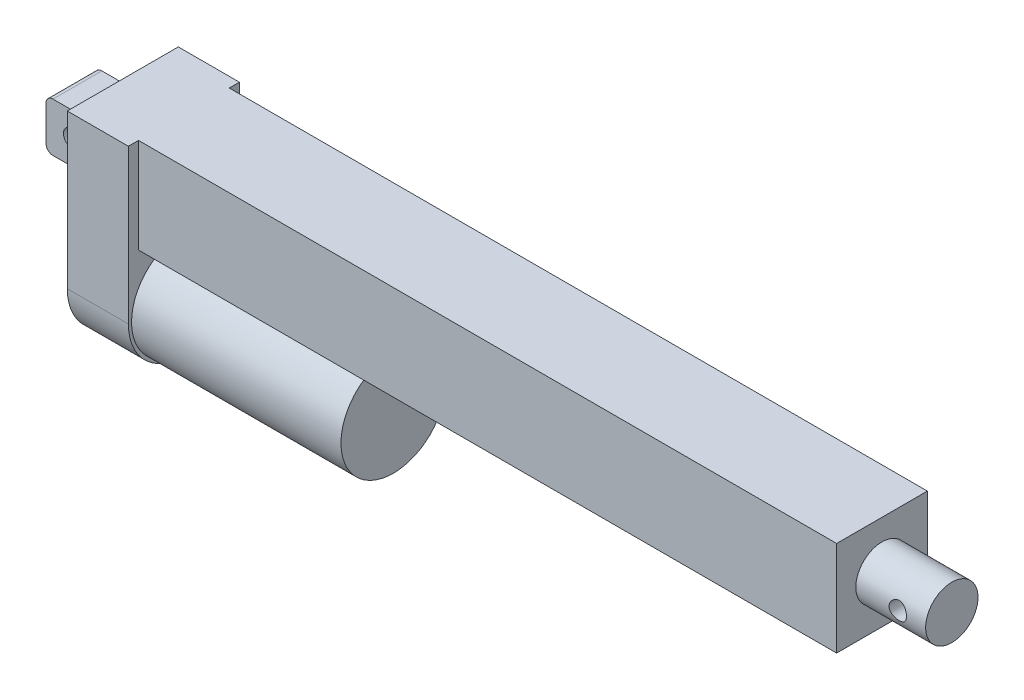
SolidWorks part; units mm, degrees
ref_plane "Front Plane" through (0, 0, 0) normal (0, 0, 1) x (1, 0, 0)
ref_plane "Top Plane" through (0, 0, 0) normal (0, 1, 0) x (1, 0, 0)
ref_plane "Right Plane" through (0, 0, 0) normal (1, 0, 0) x (0, 0, -1)
sketch "Sketch1" plane through (0, 0, 0) normal (1, 0, 0) x (0, 0, -1)
  circle A0 centre (0, 0) radius 9.525
  dimension "D1" = 19.05
extrude "Boss-Extrude1" add sketch "Sketch1" along normal blind 25.4
sketch "Sketch2" plane through (0, 0, 0) normal (0, 0, 1) x (1, 0, 0)
  line L0 (25.4, -9.525) -> (25.4, 9.525) construction
  circle A0 centre (15.24, 0) radius 3.175
  dimension "D1" = 6.35
  dimension "D2" = 10.16
extrude "Cut-Extrude1" cut sketch "Sketch2" against normal through all both and the other way through all
sketch "Sketch3" plane through (0, 0, 0) normal (-1, 0, 0) x (0, 0, 1)
  line L1 (-16.51, 17.272) -> (16.51, 17.272)
  line L2 (-16.51, 17.272) -> (-16.51, -17.272)
  line L3 (-16.51, -17.272) -> (16.51, -17.272)
  line L4 (16.51, 17.272) -> (16.51, -17.272)
  line L5 (-16.51, 17.272) -> (16.51, -17.272) construction
  line L6 (-16.51, -17.272) -> (16.51, 17.272) construction
  point P0 (0, 0)
  dimension "D1" = 34.544
  dimension "D2" = 33.02
extrude "Boss-Extrude2" add sketch "Sketch3" along normal blind 254
sketch "Sketch4" plane through (-254, 0, 0) normal (-1, 0, 0) x (0, 0, 1)
  line L1 (-20.193, 17.272) -> (20.193, 17.272)
  line L2 (-20.193, 17.272) -> (-20.193, -38.735)
  line L4 (20.193, 17.272) -> (20.193, -38.735)
  line L5 (-20.193, 17.272) -> (18.0619, -47.7642) construction
  line L6 (-18.0501, -47.7876) -> (20.193, 17.272) construction
  line L8 (16.51, 17.272) -> (-16.51, 17.272) construction
  arc A1 (-20.193, -38.735) -> (20.193, -38.735) centre (0, -38.735) ccw
  point P0 (0, -9.7283)
  point P1 (0, -58.928)
  point P14 (0, 17.272)
  dimension "D1" = 40.386
  dimension "D2" = 56.007
extrude "Boss-Extrude3" add sketch "Sketch4" along normal blind 22.225
sketch "Sketch5" plane through (-254, 0, 0) normal (1, 0, 0) x (0, 0, -1)
  circle A0 centre (0, -38.735) radius 19.05
  arc A1 (-20.193, -38.735) -> (20.193, -38.735) centre (0, -38.735) ccw construction
  dimension "D1" = 38.1
extrude "Boss-Extrude4" add sketch "Sketch5" along normal blind 76.2
sketch "Sketch6" plane through (0, 0, 0) normal (0, 0, 1) x (1, 0, 0)
  line L0 (-276.225, -38.735) -> (-276.225, 17.272) construction
  line L1 (-276.225, -10.668) -> (-295.275, -10.668)
  line L2 (-276.225, -10.668) -> (-276.225, 7.112)
  line L3 (-276.225, 7.112) -> (-295.275, 7.112)
  line L4 (-295.275, -10.668) -> (-295.275, 7.112)
  line L5 (-276.225, 17.272) -> (-254, 17.272) construction
  line L6 (-295.275, 7.112) -> (-276.225, -10.668) construction
  circle A0 centre (-285.75, -1.778) radius 3.175
  dimension "D4" = 6.35
  dimension "D1" = 10.16
  dimension "D2" = 19.05
  dimension "D3" = 17.78
extrude "Boss-Extrude5" add sketch "Sketch6" along normal mid plane 17.78
fillet "Fillet1" radius 2.54 6 edges at (-276.225, -10.668, 0) (-276.225, -1.778, -8.89) (-276.225, -1.778, 8.89) (-276.225, 7.112, 0) (-295.275, -10.668, 0) (-295.275, 7.112, 0)
equation "\"LENGTH\"= 1"
equation "\"D1@Boss-Extrude1\"=\"LENGTH\""
